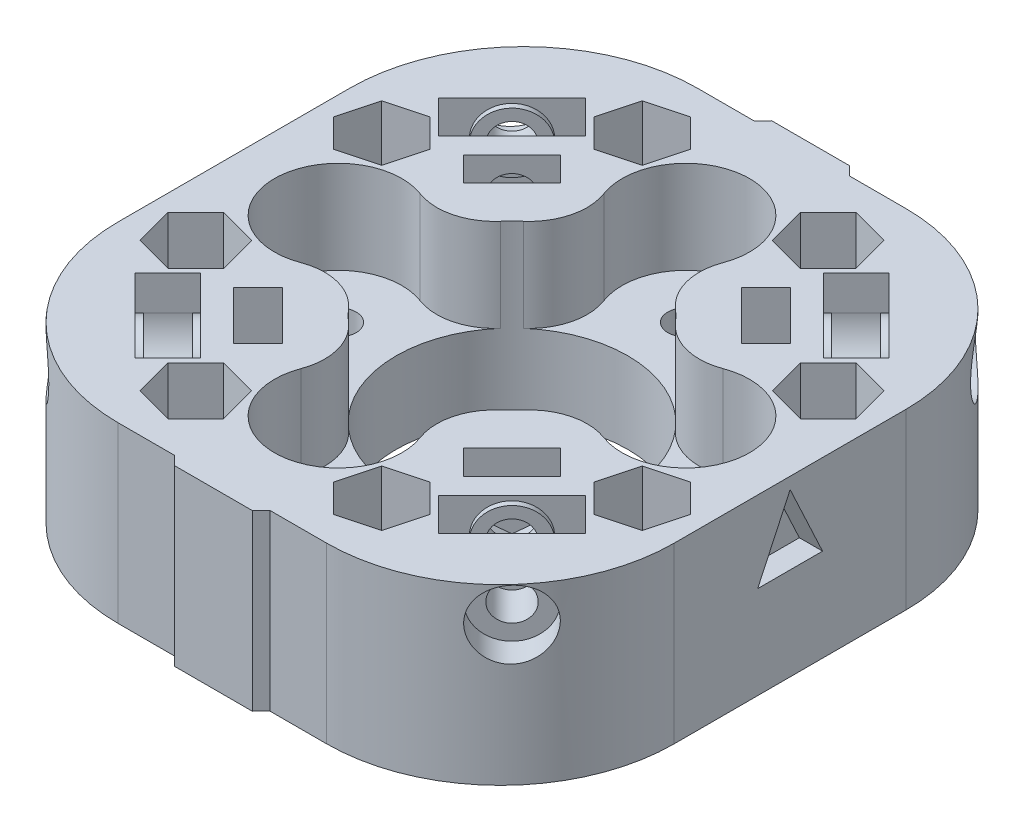
SolidWorks part; units mm, degrees
ref_plane "Alzado" through (0, 0, 0) normal (0, 0, 1) x (1, 0, 0)
ref_plane "Planta" through (0, 0, 0) normal (0, 1, 0) x (1, 0, 0)
ref_plane "Vista lateral" through (0, 0, 0) normal (1, 0, 0) x (0, 0, -1)
sketch "Croquis1" plane through (0, 0, 0) normal (0, 1, 0) x (1, 0, 0)
  line L0 (-3.36, 25.77) -> (-4.5504, 24.5824)
  line L1 (-4.5504, 24.5824) -> (-3.36, 25.77)
  line L3 (-3.36, 25.77) -> (3.36, 25.77)
  line L4 (3.36, 25.77) -> (4.5436, 24.5837)
  line L5 (0, -77.7733) -> (0, 77.7733) construction
  line L6 (0, 0) -> (18.4151, 0) construction
  line L7 (-3.36, 25.77) -> (-4.5436, 24.5837)
  line L8 (4.5504, 24.5824) -> (3.36, 25.77)
  line L9 (3.36, 25.77) -> (4.5504, 24.5824)
  line L10 (-3.36, 25.77) -> (-4.5504, 24.5824)
  line L11 (-4.5504, 24.5824) -> (-3.36, 25.77)
  line L12 (3.36, 25.77) -> (4.5436, 24.5837)
  line L13 (-3.36, 25.77) -> (-4.5436, 24.5837)
  line L14 (4.5504, 24.5824) -> (3.36, 25.77)
  line L15 (3.36, 25.77) -> (4.5504, 24.5824)
  line L16 (3.36, -25.77) -> (4.5504, -24.5824)
  line L17 (4.5504, -24.5824) -> (3.36, -25.77)
  line L18 (-3.36, -25.77) -> (-4.5436, -24.5837)
  line L19 (3.36, -25.77) -> (4.5436, -24.5837)
  line L20 (-4.5504, -24.5824) -> (-3.36, -25.77)
  line L21 (-3.36, -25.77) -> (-4.5504, -24.5824)
  line L22 (3.36, -25.77) -> (4.5504, -24.5824)
  line L23 (4.5504, -24.5824) -> (3.36, -25.77)
  line L24 (-3.36, -25.77) -> (-4.5436, -24.5837)
  line L25 (3.36, -25.77) -> (4.5436, -24.5837)
  line L26 (-3.36, -25.77) -> (3.36, -25.77)
  line L27 (-4.5504, -24.5824) -> (-3.36, -25.77)
  line L28 (-3.36, -25.77) -> (-4.5504, -24.5824)
  line L29 (24, 7) -> (24, -7)
  line L31 (-24, -7) -> (-24, 7)
  arc A0 (-4.5504, 24.5824) -> (-24, 7) centre (0, 0) ccw
  arc A1 (4.5504, 24.5824) -> (24, 7) centre (0, 0) cw
  arc A2 (-4.5504, 24.5824) -> (-24, 7) centre (0, 0) ccw
  arc A3 (4.5504, 24.5824) -> (24, 7) centre (0, 0) cw
  arc A4 (4.5504, -24.5824) -> (24, -7) centre (0, 0) ccw
  arc A5 (-4.5504, -24.5824) -> (-24, -7) centre (0, 0) cw
  arc A6 (4.5504, -24.5824) -> (24, -7) centre (0, 0) ccw
  arc A7 (-4.5504, -24.5824) -> (-24, -7) centre (0, 0) cw
  arc A8 (-24, -7) -> (24, -7) centre (0, 0) ccw
  arc A9 (-24, 7) -> (-4.5436, 24.5837) centre (0, 0) cw
  arc A10 (-24, -7) -> (24, -7) centre (0, 0) ccw
  arc A11 (-24, 7) -> (-4.5436, 24.5837) centre (0, 0) cw
  arc A12 (-24, -7) -> (-4.5436, -24.5837) centre (0, 0) ccw
  arc A13 (-24, 7) -> (24, 7) centre (0, 0) cw
  arc A14 (-24, -7) -> (-4.5436, -24.5837) centre (0, 0) ccw
  arc A15 (-24, 7) -> (24, 7) centre (0, 0) cw
  arc A16 (24, -7) -> (-24, -7) centre (0, 0) cw
  arc A17 (24, -7) -> (-24, -7) centre (0, 0) cw
  arc A18 (24, 7) -> (-24, 7) centre (0, 0) ccw
  arc A19 (24, 7) -> (-24, 7) centre (0, 0) ccw
  arc A20 (24, 7) -> (4.5436, 24.5837) centre (0, 0) ccw
  arc A21 (24, 7) -> (4.5436, 24.5837) centre (0, 0) ccw
  arc A22 (24, -7) -> (4.5436, -24.5837) centre (0, 0) cw
  arc A23 (24, -7) -> (4.5436, -24.5837) centre (0, 0) cw
  point P17 (0, 25.77)
  dimension "D1" = 3.36
  dimension "D2" = 9.094
  dimension "D3" = 4.5436
  dimension "D4" = 25.77
  dimension "D5" = 24
  dimension "D6" = 24
extrude "Saliente-Extruir1" add sketch "Croquis1" along normal blind 15
sketch "Sketch1" plane through (0, 0, 0) normal (0, -1, 0) x (1, 0, 0)
  line L1 (-9, -25) -> (9, -25)
  line L2 (-24, -10) -> (-24, 10)
  line L3 (-9, 25) -> (9, 25)
  line L4 (24, -10) -> (24, 10)
  line L5 (-24, -25) -> (24, 25) construction
  line L6 (-24, 25) -> (24, -25) construction
  arc A0 (-9, -25) -> (-24, -10) centre (-9, -10) cw
  arc A1 (9, -25) -> (24, -10) centre (9, -10) ccw
  arc A2 (9, 25) -> (24, 10) centre (9, 10) cw
  arc A3 (-24, 10) -> (-9, 25) centre (-9, 10) cw
  point P0 (0, 0)
  dimension "D3" = 15
  dimension "D1" = 50
  dimension "D2" = 48
extrude "Boss-Extrude1" add sketch "Sketch1" against normal blind 15
ref_plane "Plano1" through (0, 0, 0) normal (-0.7071, 0, 0.7071) x (0.7071, 0, 0.7071)
ref_plane "Plano2" through (16.2635, 0, -16.2635) normal (-0.7071, 0, 0.7071) x (0.7071, 0, 0.7071)
sketch "Croquis3" plane through (16.2635, 0, -16.2635) normal (-0.7071, 0, 0.7071) x (0.7071, 0, 0.7071)
  line L0 (-25, 15) -> (25, 15) construction
  line L1 (0, 0) -> (0, 15) construction
  line L4 (25, 15) -> (25, -8.8122) construction
  line L6 (-4.5, 12) -> (-4.5, 15)
  line L7 (-4.5, 15) -> (4.5, 15)
  line L8 (4.5, 12) -> (4.5, 15)
  arc A0 (-4.5, 12) -> (4.5, 12) centre (0, 12) ccw
  circle A1 centre (0, 12) radius 4 construction
  point P11 (0, 15)
  dimension "D1" = 4.5
  dimension "D2" = 8
  dimension "D3" = 3
  dimension "D4" = 50
extrude "Cortar-Extruir1" cut sketch "Croquis3" along normal blind 4
ref_plane "Plano3" through (12.0208, 0, -12.0208) normal (0.7071, 0, -0.7071) x (-0.7071, 0, -0.7071)
sketch "Croquis4" plane through (12.0208, 0, -12.0208) normal (0.7071, 0, -0.7071) x (-0.7071, 0, -0.7071)
  line L0 (-4.5, 15) -> (4.5, 15) construction
  line L1 (-2.95, 10.2968) -> (0, 8.5936)
  line L2 (0, 8.5936) -> (2.95, 10.2968)
  line L3 (2.95, 10.2968) -> (2.95, 13.7032)
  line L4 (2.95, 13.7032) -> (0, 15.4064) construction
  line L5 (0, 15.4064) -> (-2.95, 13.7032) construction
  line L6 (-2.95, 13.7032) -> (-2.95, 10.2968)
  line L8 (-2.95, 13.7032) -> (-2.95, 15)
  line L9 (-2.95, 15) -> (2.95, 15)
  line L10 (2.95, 13.7032) -> (2.95, 15)
  circle A0 centre (0, 12) radius 2.95 construction
  arc A1 (-4.5, 12) -> (4.5, 12) centre (0, 12) ccw construction
  dimension "D1" = 5.9
extrude "Cortar-Extruir2" cut sketch "Croquis4" against normal blind 3
sketch "Croquis5" plane through (12.0208, 0, -12.0208) normal (-0.7071, 0, 0.7071) x (0.7071, 0, 0.7071)
  circle A0 centre (0, 12) radius 1.6
  arc A2 (-4.5, 12) -> (4.5, 12) centre (0, 12) ccw construction
  dimension "D1" = 3.2
extrude "Cortar-Extruir3" cut sketch "Croquis5" against normal through all
sketch "Croquis6" [suppressed] plane through (24, 0, 0) normal (1, 0, 0) x (0, 0, -1)
  line L0 (0, 14.9) -> (-2.8, 8.9)
  line L1 (-2.8, 8.9) -> (2.8, 8.9)
  line L2 (2.8, 8.9) -> (0, 14.9)
  line L3 (0, 15) -> (0, 0) construction
  line L5 (7, 15) -> (-7, 15) construction
  point P10 (0, 15)
  point P12 (0, 8.9)
  dimension "D1" = 6
  dimension "D2" = 5.6
  dimension "D3" = 0.1
extrude "Cortar-Extruir4" [suppressed] cut sketch "Croquis6" against normal blind 2
ref_plane "Plano4" through (21.2132, 0, -21.2132) normal (0.7071, 0, -0.7071) x (-0.7071, 0, -0.7071)
sketch "Croquis8" plane through (21.2132, 0, -21.2132) normal (0.7071, 0, -0.7071) x (-0.7071, 0, -0.7071)
  circle A0 centre (0, 12) radius 2.95
  dimension "D1" = 5.9
extrude "Cortar-Extruir5" cut sketch "Croquis8" against normal blind 4
sketch "Croquis10" plane through (13.435, 0, -13.435) normal (0.7071, 0, -0.7071) x (-0.7071, 0, -0.7071)
  circle A0 centre (0, 12) radius 2.6
  circle A1 centre (0, 12) radius 1.6 construction
  circle A2 centre (0, 12) radius 1.6
  dimension "D1" = 1
extrude "Saliente-Extruir2" add sketch "Croquis10" along normal blind 0.5
sketch "Croquis11" plane through (16.2635, 0, -16.2635) normal (-0.7071, 0, 0.7071) x (0.7071, 0, 0.7071)
  circle A0 centre (0, 12) radius 1.6
  circle A1 centre (0, 12) radius 1.6 construction
  circle A2 centre (0, 12) radius 2.6
  circle A3 centre (0, 12) radius 2.6 construction
extrude "Saliente-Extruir3" add sketch "Croquis11" along normal blind 0.5
sketch "Croquis12" plane through (0, 0, 0) normal (0, -1, 0) x (1, 0, 0)
  line L0 (0, -15) -> (0, 0) construction
  line L1 (-15, 0) -> (0, 0) construction
  line L2 (0, 15) -> (0, 0) construction
  line L3 (15, 0) -> (0, 0) construction
  circle A0 centre (0, 0) radius 10
  circle A1 centre (0, -15) radius 1.55
  circle A4 centre (-15, 0) radius 1.55
  circle A5 centre (0, 15) radius 1.55
  circle A6 centre (15, 0) radius 1.55
  point P15 (0, 0)
  dimension "D1" = 20
  dimension "D2" = 3.1
  dimension "D3" = 15
extrude "Cortar-Extruir6" cut sketch "Croquis12" against normal through all
sketch "Croquis13" plane through (0, 15, 0) normal (0, 1, 0) x (1, 0, 0)
  line L0 (0, 15) -> (0, 0) construction
  line L1 (15, 0) -> (0, 0) construction
  line L2 (0, -15) -> (0, 0) construction
  line L3 (-15, 0) -> (0, 0) construction
  arc A0 (13.075, -5.1521) -> (7.55, -6.5572) centre (11.325, -9.8359) ccw
  arc A1 (-6.5572, 7.55) -> (6.5572, 7.55) centre (0, 0) ccw
  arc A2 (5.1521, 13.075) -> (6.5572, 7.55) centre (9.8359, 11.325) ccw
  arc A3 (-5.1521, 13.075) -> (-6.5572, 7.55) centre (-9.8359, 11.325) cw
  arc A4 (13.075, 5.1521) -> (7.55, 6.5572) centre (11.325, 9.8359) cw
  arc A5 (5.1521, 13.075) -> (-5.1521, 13.075) centre (0, 15) ccw
  arc A6 (13.075, -5.1521) -> (13.075, 5.1521) centre (15, 0) ccw
  arc A7 (-5.1521, -13.075) -> (-6.5572, -7.55) centre (-9.8359, -11.325) ccw
  arc A8 (5.1521, -13.075) -> (6.5572, -7.55) centre (9.8359, -11.325) cw
  arc A9 (-5.1521, -13.075) -> (5.1521, -13.075) centre (0, -15) ccw
  arc A10 (-13.075, 5.1521) -> (-7.55, 6.5572) centre (-11.325, 9.8359) ccw
  arc A11 (-13.075, -5.1521) -> (-7.55, -6.5572) centre (-11.325, -9.8359) cw
  arc A12 (-13.075, 5.1521) -> (-13.075, -5.1521) centre (-15, 0) ccw
  point P33 (0, 0)
  circle M1 centre (15, 0) radius 1.55
  circle M2 centre (0, -15) radius 1.55
  circle M3 centre (-15, 0) radius 1.55
  circle M4 centre (0, 15) radius 1.55
  circle M5 centre (0, 0) radius 10
  dimension "D1" = 5.5
  dimension "D3" = 20
  dimension "D4" = 5
  dimension "D5" = 5
  dimension "D2" = 15
extrude "Cortar-Extruir7" cut sketch "Croquis13" against normal blind 8 contours A2 A5 A3 M5 M4 | A1 M5 | A7 A9 A8 A1 M2 | A10 A12 A11 M5 M3 | A0 A6 A4 A1 M1
pattern_circular "MatrizC1" count 4 over 360 about axis through (0, 0, 0) along (0, 1, 0) of "Cortar-Extruir5", "Cortar-Extruir3", "Saliente-Extruir2", "Cortar-Extruir1", "Cortar-Extruir2", "Saliente-Extruir3"
sketch "Croquis14" plane through (0, 0, 0) normal (0, -1, 0) x (1, 0, 0)
  circle A0 centre (0, -15) radius 2.95
  dimension "D1" = 5.9
extrude "Cortar-Extruir8" cut sketch "Croquis14" against normal blind 3
pattern_circular "MatrizC2" count 4 every 90 about axis through (0, 0, 0) along (0, 1, 0) of "Cortar-Extruir8"
sketch "Croquis15" plane through (0, 0, 0) normal (0, -1, 0) x (1, 0, 0)
  line L0 (0, 0) -> (-10.6066, 10.6066) construction
  line L1 (-10.6066, 10.6066) -> (0, 0) construction
  line L2 (0, 0) -> (0, 17.95) construction
  circle A0 centre (-10.6066, 10.6066) radius 1.5
  circle A1 centre (0, 15) radius 2.95 construction
  dimension "D1" = 3
  dimension "D2" = 45
  dimension "D3" = 15
extrude "Cortar-Extruir9" cut sketch "Croquis15" against normal blind 5
pattern_circular "MatrizC3" count 4 every 90 about axis through (0, 0, 0) along (0, 1, 0) of "Cortar-Extruir9"
sketch "Croquis16" plane through (0, 15, 0) normal (0, 1, 0) x (1, 0, 0)
  line L0 (-10.253, 16.617) -> (-13.0815, 19.4454) construction
  line L1 (-4.7331, 20.148) -> (-7.1418, 22.5567)
  line L2 (-7.1418, 22.5567) -> (-10.4321, 21.6751)
  line L3 (-10.4321, 21.6751) -> (-11.3137, 18.3848)
  line L4 (-11.3137, 18.3848) -> (-8.905, 15.9761)
  line L5 (-8.905, 15.9761) -> (-5.6147, 16.8577)
  line L6 (-5.6147, 16.8577) -> (-4.7331, 20.148)
  line L7 (-13.0815, 19.4454) -> (-19.4454, 13.0815) construction
  line L8 (-16.617, 10.253) -> (-19.4454, 13.0815) construction
  line L9 (-18.3848, 11.3137) -> (-21.6751, 10.4321)
  line L10 (-21.6751, 10.4321) -> (-22.5567, 7.1418)
  line L11 (-22.5567, 7.1418) -> (-20.148, 4.7331)
  line L12 (-20.148, 4.7331) -> (-16.8577, 5.6147)
  line L13 (-16.8577, 5.6147) -> (-15.9761, 8.905)
  line L14 (-15.9761, 8.905) -> (-18.3848, 11.3137)
  circle A0 centre (-8.0234, 19.2664) radius 2.95 construction
  circle A1 centre (-8.0234, 19.2664) radius 1.6
  circle A2 centre (-19.2664, 8.0234) radius 2.95 construction
  circle A3 centre (-19.2664, 8.0234) radius 1.6
  dimension "D4" = 3.2
  dimension "D8" = 3.2
  dimension "D1" = 0.5
  dimension "D2" = 5.9
  dimension "D3" = 2
  dimension "D5" = 0.5
  dimension "D6" = 2
  dimension "D7" = 5.9
extrude "Cortar-Extruir10" cut sketch "Croquis16" against normal blind 10
sketch "Croquis17" plane through (0, 15, 0) normal (0, 1, 0) x (1, 0, 0)
  circle A0 centre (-19.2664, 8.0234) radius 1.6 construction
  circle A1 centre (-8.0234, 19.2664) radius 1.6 construction
  circle A2 centre (-19.2664, 8.0234) radius 1.6
  circle A3 centre (-8.0234, 19.2664) radius 1.6
extrude "Cortar-Extruir11" cut sketch "Croquis17" against normal through all
pattern_circular "MatrizC4" count 4 every 90 about axis through (0, 0, 0) along (0, 1, 0) of "Cortar-Extruir10", "Cortar-Extruir11"
sketch "Sketch2" plane through (24, 0, 0) normal (1, 0, 0) x (0, 0, -1)
  line L1 (0, 14) -> (-2.8, 8)
  line L2 (-2.8, 8) -> (2.8, 8)
  line L3 (2.8, 8) -> (0, 14)
  line L4 (0, 14) -> (0, 15) construction
  line L5 (10, 15) -> (-10, 15) construction
  dimension "D1" = 5.6
  dimension "D2" = 6
  dimension "D3" = 1
extrude "Cut-Extrude10" cut sketch "Sketch2" against normal blind 2 contours L1 L2 L3
